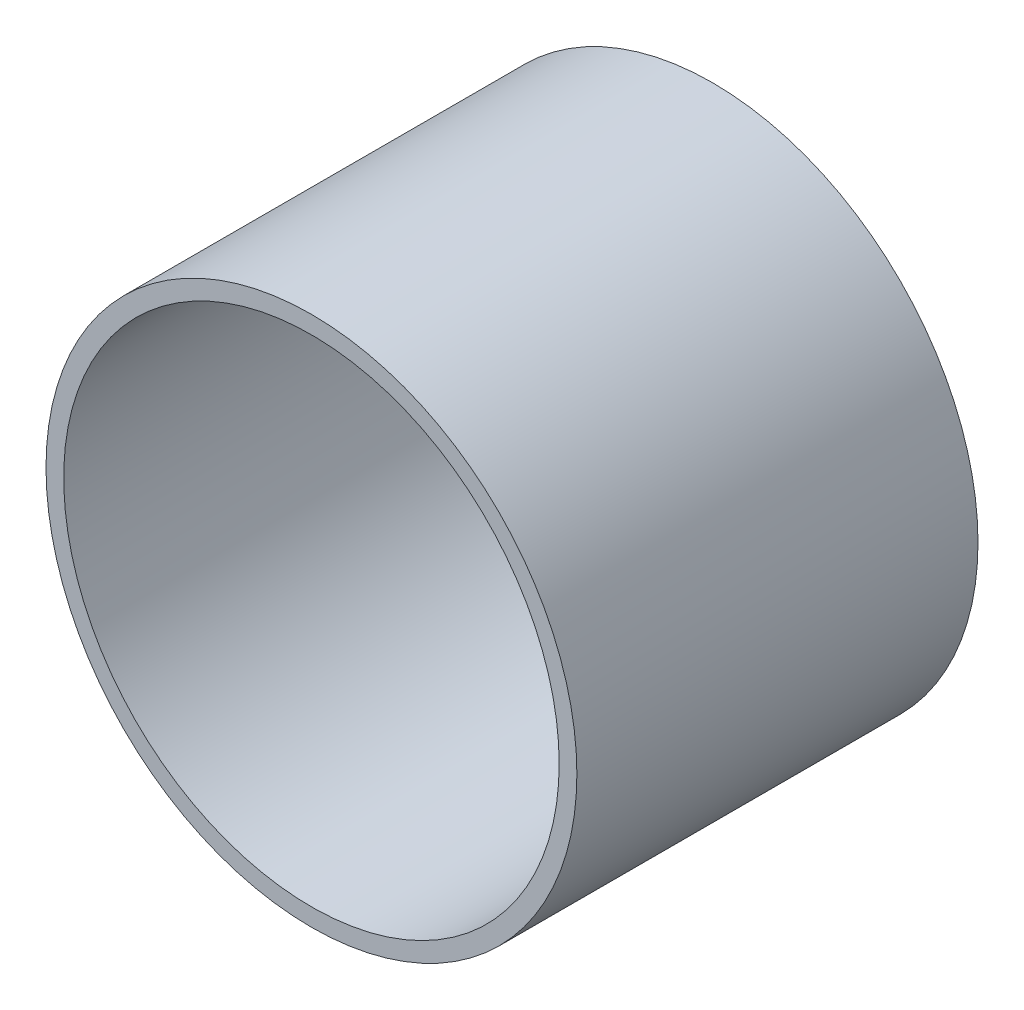
SolidWorks part; units mm, degrees
ref_plane "前视基准面" through (0, 0, 0) normal (0, 0, 1) x (1, 0, 0)
ref_plane "上视基准面" through (0, 0, 0) normal (0, 1, 0) x (1, 0, 0)
ref_plane "右视基准面" through (0, 0, 0) normal (1, 0, 0) x (0, 0, -1)
other "Configuration Table"
sketch "草图1" plane through (0, 0, 0) normal (1, 0, 0) x (0, 0, -1)
  line L0 (132, 0) -> (210, 0) construction
  line L1 (205, 42) -> (205, 45)
  line L2 (205, 45) -> (137, 45)
  line L3 (137, 45) -> (137, 42)
  line L4 (137, 42) -> (205, 42)
revolve "旋转1" add sketch "草图1" angle 360 about L0
